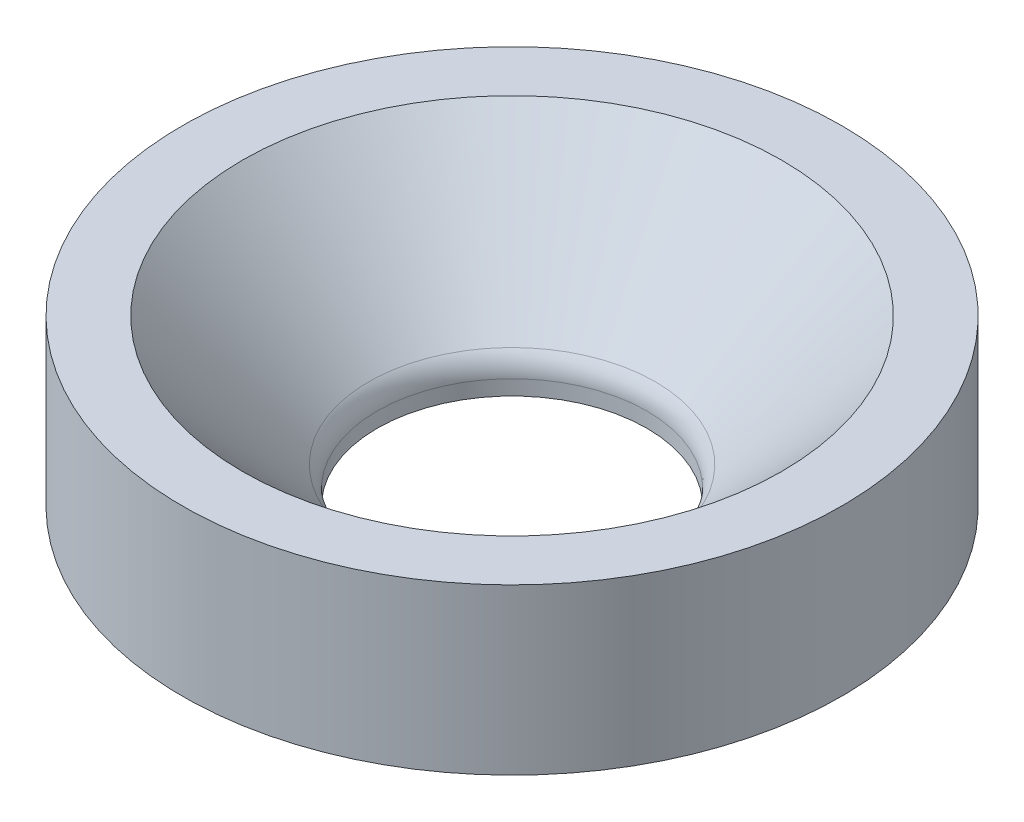
SolidWorks part; units mm, degrees
ref_plane "Plan de face" through (0, 0, 0) normal (0, 0, 1) x (1, 0, 0)
ref_plane "Plan de dessus" through (0, 0, 0) normal (0, 1, 0) x (1, 0, 0)
ref_plane "Plan de droite" through (0, 0, 0) normal (1, 0, 0) x (0, 0, -1)
sketch "Esquisse2" plane through (0, 0, 0) normal (0, 0, 1) x (1, 0, 0)
  line L0 (-9, 0) -> (-22, 0)
  line L3 (-22, 0) -> (-22, 11)
  line L6 (-18, 11) -> (-9.5716, 2.3999)
  line L7 (-9, 1) -> (-9, 0)
  line L8 (0, 0) -> (0, 16) construction
  line L9 (-22, 11) -> (-18, 11)
  arc A0 (-9.5716, 2.3999) -> (-9, 1) centre (-11, 1) cw
  point P13 (-9, 1.8166)
  dimension "D9" = 2
  dimension "D1" = 22
  dimension "D2" = 1
  dimension "D3" = 9
  dimension "D4" = 18
  dimension "D5" = 11
revolve "Révolution1" add sketch "Esquisse2" angle 360 about L8
